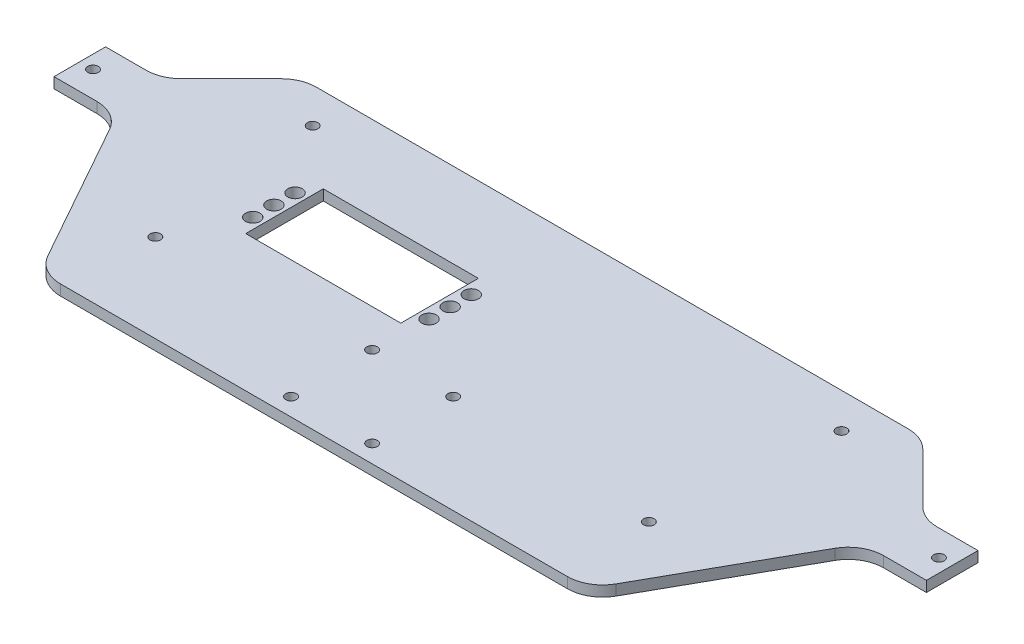
SolidWorks part; units mm, degrees
ref_plane "Alzado" through (0, 0, 0) normal (0, 0, 1) x (1, 0, 0)
ref_plane "Planta" through (0, 0, 0) normal (0, 1, 0) x (1, 0, 0)
ref_plane "Vista lateral" through (0, 0, 0) normal (1, 0, 0) x (0, 0, -1)
sketch "Croquis1" plane through (0, 0, 0) normal (0, 1, 0) x (1, 0, 0)
  line L0 (-27.8825, 0) -> (38.5584, 0) construction
  line L1 (-88.1, 42.3182) -> (88.1, 42.3182)
  line L2 (-77.75, -42.3182) -> (77.75, -42.3182)
  line L3 (-88.1, 42.3182) -> (-108.1, 22.3182)
  line L4 (-108.1, 22.3182) -> (-127.75, 22.3182)
  line L5 (0, 0) -> (0, 27.7067) construction
  line L6 (-127.75, 22.3182) -> (-127.75, 7.6818)
  line L7 (-127.75, 7.6818) -> (-105.75, 7.6818)
  line L8 (-105.75, 7.6818) -> (-77.75, -42.3182)
  line L9 (88.1, 42.3182) -> (108.1, 22.3182)
  line L10 (108.1, 22.3182) -> (127.75, 22.3182)
  line L11 (127.75, 22.3182) -> (127.75, 7.6818)
  line L12 (127.75, 7.6818) -> (105.75, 7.6818)
  line L13 (105.75, 7.6818) -> (77.75, -42.3182)
  dimension "D1" = 255.5
  dimension "D2" = 84.6363
  dimension "D3" = 19.65
  dimension "D4" = 22
  dimension "D5" = 22
  dimension "D6" = 50
  dimension "D7" = 50
  dimension "D8" = 50
  dimension "D9" = 20
  dimension "D10" = 20
  dimension "D11" = 19.65
extrude "Saliente-Extruir1" add sketch "Croquis1" along normal blind 3
fillet "Redondeo1" radius 10 8 edges at (88.1, 1.5, -42.3182) (-88.1, 1.5, -42.3182) (-77.75, 1.5, 42.3182) (77.75, 1.5, 42.3182) (108.1, 1.5, -22.3182) (105.75, 1.5, -7.6818) (-105.75, 1.5, -7.6818) (-108.1, 1.5, -22.3182)
sketch "Croquis2" plane through (0, 3, 0) normal (0, 1, 0) x (1, 0, 0)
  line L0 (0, 0) -> (0, -87.7887) construction
  line L1 (-119.9961, 22.3182) -> (-119.9961, 40.4374) construction
  line L2 (-112.2421, 22.3182) -> (-127.75, 22.3182) construction
  line L3 (-127.75, 15) -> (-123.2915, 15) construction
  line L4 (-127.75, 22.3182) -> (-127.75, 7.6818) construction
  line L5 (119.9961, 22.3182) -> (119.9961, 29.1715) construction
  line L6 (127.75, 22.3182) -> (112.2421, 22.3182) construction
  line L7 (115.6048, 15) -> (126.3231, 15) construction
  line L8 (83.9579, 42.3182) -> (-83.9579, 42.3182) construction
  line L9 (-57, 17.3182) -> (-15, 17.3182)
  line L10 (-71.8888, -42.3182) -> (71.8888, -42.3182) construction
  line L11 (-15, 17.3182) -> (-15, -2.6818)
  line L12 (-15, -2.6818) -> (-57, -2.6818)
  line L13 (-57, -2.6818) -> (-57, 17.3182)
  line L14 (-57, 7.3182) -> (-2.6959, 7.3182) construction
  line L15 (-36, 17.3182) -> (-36, 33.9331) construction
  line L16 (-11, 7.3182) -> (-11, 14.1752) construction
  line L17 (-61, 7.3182) -> (-61, 4.4352) construction
  circle A0 centre (70, -17.3182) radius 1.5
  circle A1 centre (-70, -17.3182) radius 1.5
  circle A2 centre (-119.9961, 15) radius 1.5
  circle A3 centre (119.9961, 15) radius 1.5
  circle A4 centre (-75, 32.3182) radius 1.5
  circle A5 centre (75, 32.3182) radius 1.5
  circle A6 centre (-11.5, -14.3182) radius 1.5
  circle A7 centre (11.5, -14.3182) radius 1.5
  circle A8 centre (-11.5, -37.3182) radius 1.5
  circle A9 centre (11.5, -37.3182) radius 1.5
  circle A10 centre (-61, 7.3182) radius 2.05
  circle A11 centre (-11, 7.3182) radius 2.05
  circle A12 centre (-61, 13.3182) radius 2.05
  circle A13 centre (-61, 1.3182) radius 2.05
  circle A14 centre (-11, 13.3182) radius 2.05
  circle A15 centre (-11, 1.3182) radius 2.05
  dimension "D1" = 3
  dimension "D2" = 3
  dimension "D7" = 3
  dimension "D8" = 3
  dimension "D10" = 3
  dimension "D11" = 3
  dimension "D17" = 3
  dimension "D18" = 3
  dimension "D19" = 3
  dimension "D20" = 3
  dimension "D25" = 50
  dimension "D27" = 4.1
  dimension "D28" = 4.1
  dimension "D29" = 4.1
  dimension "D30" = 4.1
  dimension "D31" = 4.1
  dimension "D32" = 4.1
  dimension "D3" = 75
  dimension "D4" = 75
  dimension "D5" = 10
  dimension "D6" = 10
  dimension "D9" = 140
  dimension "D12" = 25
  dimension "D13" = 23
  dimension "D14" = 23
  dimension "D15" = 5
  dimension "D16" = 23
  dimension "D21" = 42
  dimension "D22" = 20
  dimension "D23" = 30
  dimension "D24" = 25
  dimension "D26" = 50
  dimension "D33" = 6
  dimension "D34" = 6
  dimension "D35" = 6
  dimension "D36" = 6
extrude "Cortar-Extruir1" cut sketch "Croquis2" against normal through all
sketch "Croquis3" plane through (0, 3, 0) normal (0, 1, 0) x (1, 0, 0)
  line L0 (-123.75, 22.3182) -> (-123.75, 7.6818)
  line L1 (-112.2421, 22.3182) -> (-127.75, 22.3182) construction
  line L2 (-127.75, 7.6818) -> (-111.6112, 7.6818) construction
  line L3 (-123.75, 7.6818) -> (-127.75, 7.6818)
  line L4 (-127.75, 7.6818) -> (-127.75, 22.3182)
  line L5 (-127.75, 22.3182) -> (-123.75, 22.3182)
  line L6 (127.75, 7.6818) -> (127.75, 22.3182)
  line L7 (127.75, 22.3182) -> (123.75, 22.3182)
  line L8 (127.75, 22.3182) -> (112.2421, 22.3182) construction
  line L9 (123.75, 22.3182) -> (123.75, 7.6818)
  line L10 (111.6112, 7.6818) -> (127.75, 7.6818) construction
  line L11 (123.75, 7.6818) -> (127.75, 7.6818)
  dimension "D1" = 4
  dimension "D2" = 4
extrude "Cortar-Extruir2" cut sketch "Croquis3" against normal through all
sketch "Croquis4" plane through (0, 3, 0) normal (0, 1, 0) x (1, 0, 0)
  line L0 (-36, 17.3182) -> (-36, -16.9775) construction
  line L1 (-15, 17.3182) -> (-57, 17.3182) construction
  line L2 (-57, 7.3182) -> (-47.1795, 7.3182) construction
  line L3 (-57, 17.3182) -> (-57, -2.6818) construction
  line L4 (-58, 18.3182) -> (-58, -3.6818)
  line L5 (-58, -3.6818) -> (-14, -3.6818)
  line L6 (-14, -3.6818) -> (-14, 18.3182)
  line L7 (-58, 18.3182) -> (-14, 18.3182)
  line L8 (-15, -2.6818) -> (-15, 17.3182) construction
  line L9 (-57, -2.6818) -> (-15, -2.6818) construction
  dimension "D1" = 1
  dimension "D2" = 1
  dimension "D3" = 1
  dimension "D4" = 1
extrude "Cortar-Extruir3" cut sketch "Croquis4" against normal through all
